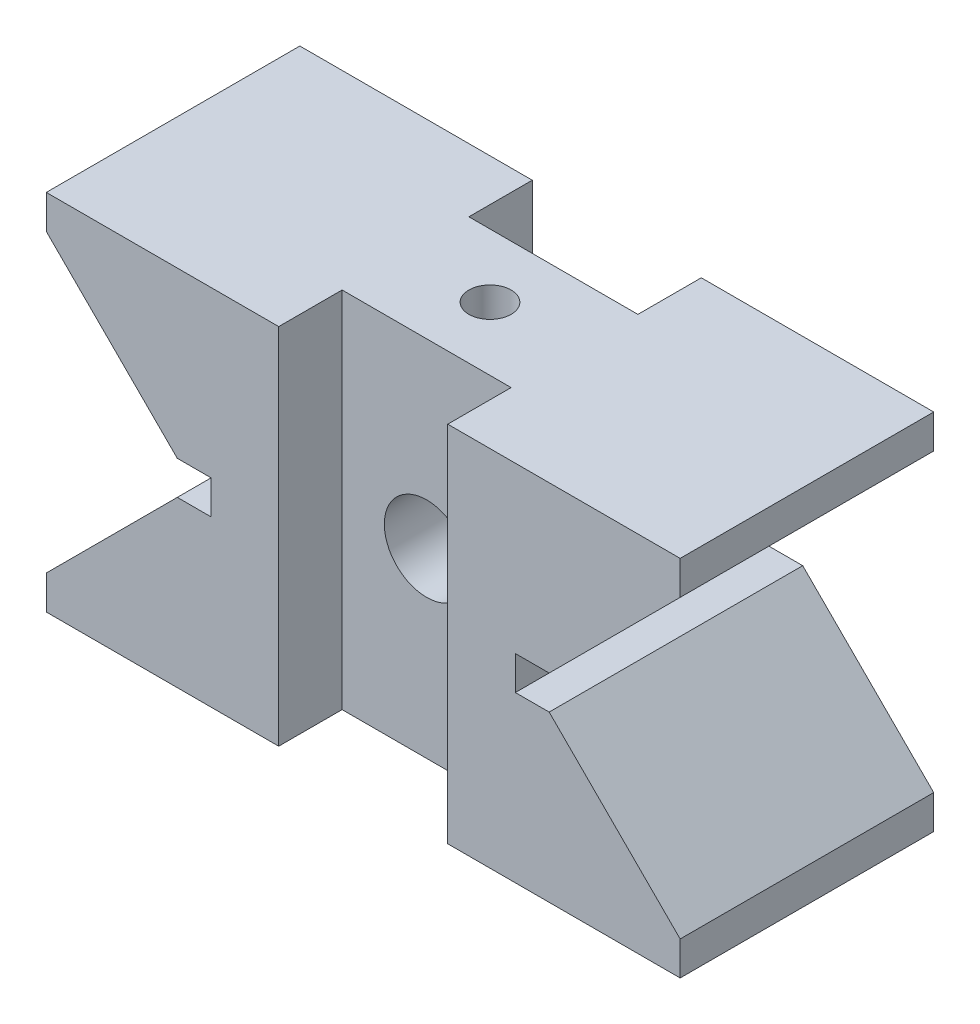
SolidWorks part; units mm, degrees
ref_plane "Plan de face" through (0, 0, 0) normal (0, 0, 1) x (1, 0, 0)
ref_plane "Plan de dessus" through (0, 0, 0) normal (0, 1, 0) x (1, 0, 0)
ref_plane "Plan de droite" through (0, 0, 0) normal (1, 0, 0) x (0, 0, -1)
sketch "Esquisse1" plane through (0, 0, 0) normal (0, 0, 1) x (1, 0, 0)
  line L0 (-75, 43) -> (75, 43)
  line L1 (75, 43) -> (75, 35)
  line L3 (36, 4) -> (36, -4)
  line L5 (75, -35) -> (75, -43)
  line L6 (75, -43) -> (-75, -43)
  line L7 (-75, -43) -> (-75, -35)
  line L9 (-36, -4) -> (-36, 4)
  line L11 (-75, 35) -> (-75, 43)
  line L12 (-75, 35) -> (-75, -35) construction
  line L13 (75, 35) -> (75, -35) construction
  line L14 (-75, -35) -> (75, -35) construction
  line L15 (75, 35) -> (-75, 35) construction
  line L16 (-36, 4) -> (36, 4) construction
  line L17 (-36, -4) -> (36, -4) construction
  line L18 (36, -4) -> (-36, 4) construction
  line L19 (-75, 43) -> (75, -43) construction
  line L20 (75, -35) -> (-75, 35) construction
  line L21 (-75, 35) -> (-44, 4)
  line L22 (-44, 4) -> (-36, 4)
  line L23 (-75, -35) -> (-44, -4)
  line L24 (-44, -4) -> (-36, -4)
  line L25 (75, 35) -> (44, 4)
  line L26 (44, 4) -> (36, 4)
  line L27 (75, -35) -> (44, -4)
  line L28 (44, -4) -> (36, -4)
  line L29 (-44, 4) -> (-44, -4) construction
  line L30 (44, 4) -> (44, -4) construction
  line L31 (-44, 4) -> (44, -4) construction
  dimension "D1" = 70
  dimension "D2" = 8
  dimension "D3" = 8
  dimension "D4" = 150
  dimension "D5" = 8
extrude "Boss.-Extru.1" add sketch "Esquisse1" along normal blind 60
sketch "Esquisse2" plane through (0, 0, 60) normal (0, 0, 1) x (1, 0, 0)
  line L0 (75, 43) -> (-75, 43) construction
  line L1 (-20, 43) -> (20, 43)
  line L2 (-20, 43) -> (-20, -43)
  line L3 (-20, -43) -> (20, -43)
  line L4 (20, 43) -> (20, -43)
  line L5 (-75, -43) -> (75, -43) construction
  line L6 (-20, 43) -> (20, -43) construction
  dimension "D1" = 40
extrude "Enlèv. mat.-Extru.1" cut sketch "Esquisse2" against normal blind 15
sketch "Esquisse3" plane through (0, 0, 0) normal (0, 0, -1) x (-1, 0, 0)
  line L0 (75, -43) -> (-75, -43) construction
  line L1 (-20, 43) -> (20, 43)
  line L2 (-20, 43) -> (-20, -43)
  line L3 (-20, -43) -> (20, -43)
  line L4 (20, 43) -> (20, -43)
  line L5 (-20, 43) -> (20, -43) construction
extrude "Enlèv. mat.-Extru.2" cut sketch "Esquisse3" against normal blind 15
sketch "Esquisse4" plane through (0, 0, 15) normal (0, 0, -1) x (-1, 0, 0)
  circle A0 centre (0, 0) radius 10
  dimension "D1" = 20
extrude "Enlèv. mat.-Extru.3" cut sketch "Esquisse4" against normal through all
sketch "Esquisse5" plane through (0, 43, 0) normal (0, 1, 0) x (1, 0, 0)
  line L0 (20, -45) -> (-20, -15) construction
  circle A0 centre (0, -30) radius 5
  dimension "D1" = 10
extrude "Enlèv. mat.-Extru.4" cut sketch "Esquisse5" against normal through all
